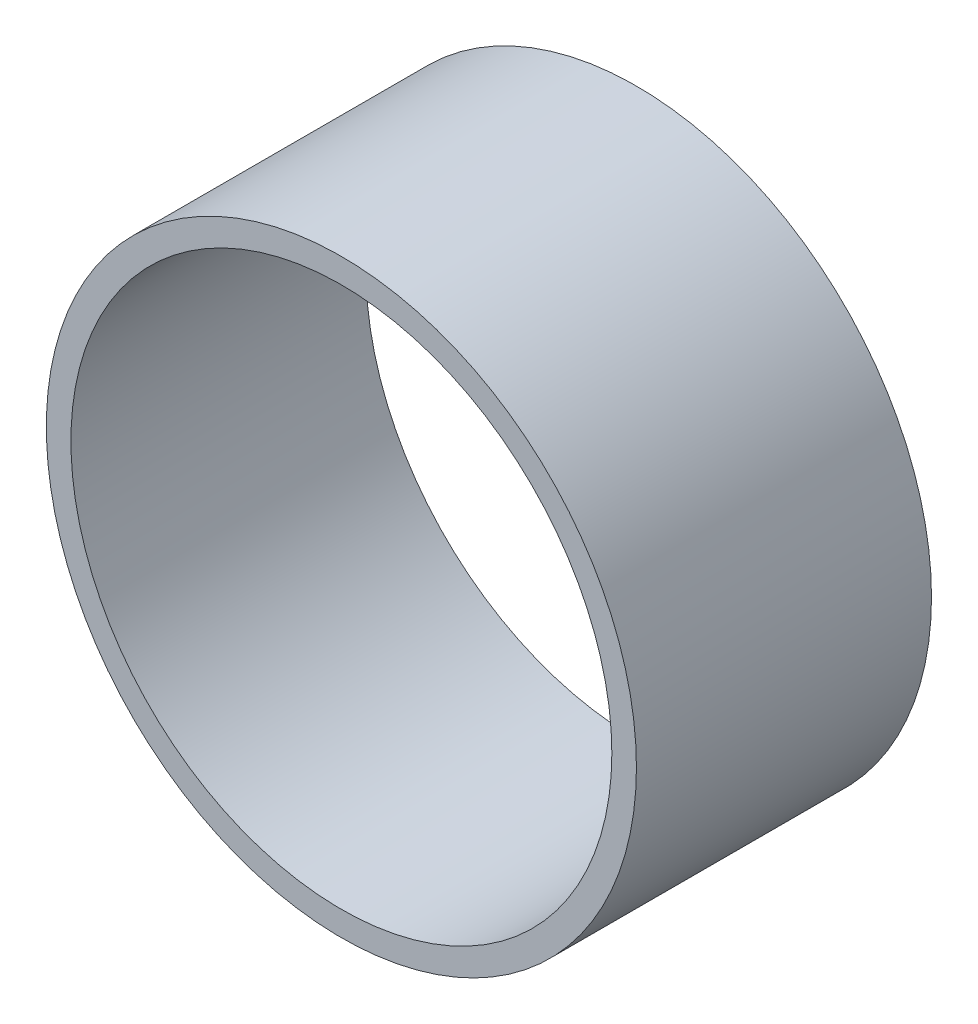
SolidWorks part; units mm, degrees
ref_plane "Plan de face" through (0, 0, 0) normal (0, 0, 1) x (1, 0, 0)
ref_plane "Plan de dessus" through (0, 0, 0) normal (0, 1, 0) x (1, 0, 0)
ref_plane "Plan de droite" through (0, 0, 0) normal (1, 0, 0) x (0, 0, -1)
sketch "Esquisse1" plane through (0, 0, 0) normal (0, 0, 1) x (1, 0, 0)
  circle A0 centre (0, 0) radius 12
  circle A1 centre (0, 0) radius 11
  dimension "D1" = 24
  dimension "D2" = 22
extrude "Boss.-Extru.1" add sketch "Esquisse1" along normal blind 12
equation "\"è.2\"=14.4"
